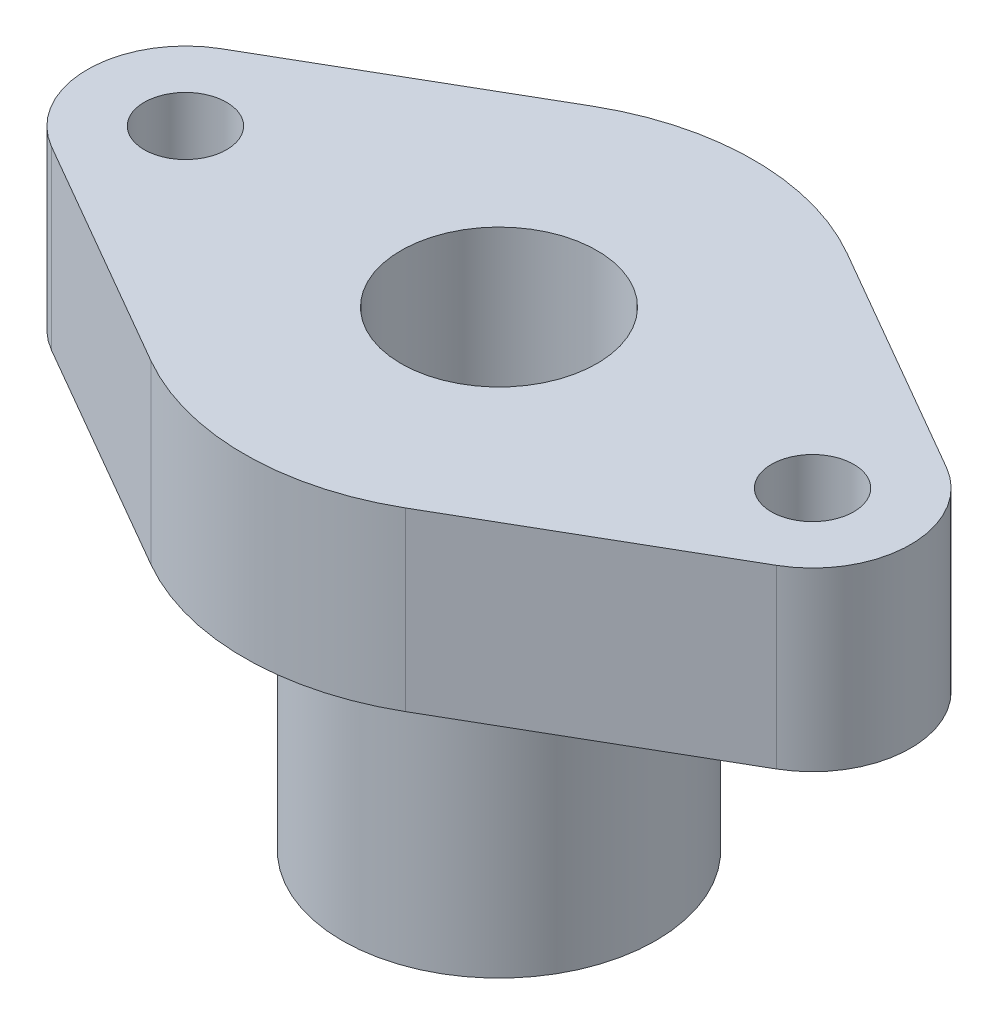
SolidWorks part; units mm, degrees
ref_plane "Front Plane" through (0, 0, 0) normal (0, 0, 1) x (1, 0, 0)
ref_plane "Top Plane" through (0, 0, 0) normal (0, 1, 0) x (1, 0, 0)
ref_plane "Right Plane" through (0, 0, 0) normal (1, 0, 0) x (0, 0, -1)
sketch "Sketch1" plane through (0, 0, 0) normal (0, 0, 1) x (1, 0, 0)
  line L0 (0, 8.3673) -> (0, -10.5612) construction
  line L1 (-8, 3.3673) -> (-8, -11.6327)
  line L2 (-8, -11.6327) -> (-5, -11.6327)
  line L3 (-5, -11.6327) -> (-5, 3.3673)
  line L4 (-5, 3.3673) -> (-8, 3.3673)
  dimension "D1" = 15
  dimension "D2" = 3
  dimension "D3" = 5
revolve "Revolve1" add sketch "Sketch1" angle 360 about L0
sketch "Sketch2" plane through (0, 3.3673, 0) normal (0, 1, 0) x (1, 0, 0)
  line L0 (-6.5, 11.2583) -> (-18.5, 4.3301)
  line L1 (6.5, 11.2583) -> (18.5, 4.3301)
  line L2 (-6.5, -11.2583) -> (-18.5, -4.3301)
  line L3 (6.5, -11.2583) -> (18.5, -4.3301)
  arc A0 (-6.5, -11.2583) -> (6.5, -11.2583) centre (0, 0) ccw
  arc A1 (-18.5, 4.3301) -> (-18.5, -4.3301) centre (-16, 0) ccw
  arc A2 (18.5, -4.3301) -> (18.5, 4.3301) centre (16, 0) ccw
  circle A3 centre (0, 0) radius 5
  arc A4 (6.5, 11.2583) -> (-6.5, 11.2583) centre (0, 0) ccw
  dimension "D1" = 26
  dimension "D2" = 10
  dimension "D3" = 10
  dimension "D4" = 16
  dimension "D5" = 16
extrude "Boss-Extrude1" add sketch "Sketch2" along normal blind 9
hole_wizard "M5x0.8 Tapped Hole1" positions "3DSketch1" profile "Sketch3" tap size "M5x0.8" standard "ANSI Metric"
sketch3d "3DSketch1"
  line L0 (-16, 12.3673, 0) -> (-16, 3.3673, 0) construction
  line L1 (16, 12.3673, 0) -> (16, 3.3673, 0) construction
  point P0 (-16, 12.3673, 0)
  point P4 (16, 12.3673, 0)
sketch "Sketch3" plane through (-16, 12.3673, 0) normal (1, 0, 0) x (0, 0, 1)
  line L0 (0, 0) -> (0, 13.6618)
  line L1 (0, 13.6618) -> (2.1, 12.4)
  line L2 (2.1, 12.4) -> (2.1, 0)
  line L5 (2.1, 0) -> (0, 0)
  line L10 (0, 13.6618) -> (-2.1, 12.4) construction
  line L11 (0, -6.35) -> (0, 107.95) construction
  dimension "Tap Drill Dia." = 4.2
  dimension "Tap Drill Depth" = 12.4
  dimension "Drill Angle" = 118
cosmetic thread "Hole Thread1" parameters "D1"=9, "D2"=5
cosmetic thread "Hole Thread2" parameters "D1"=9, "D2"=5
